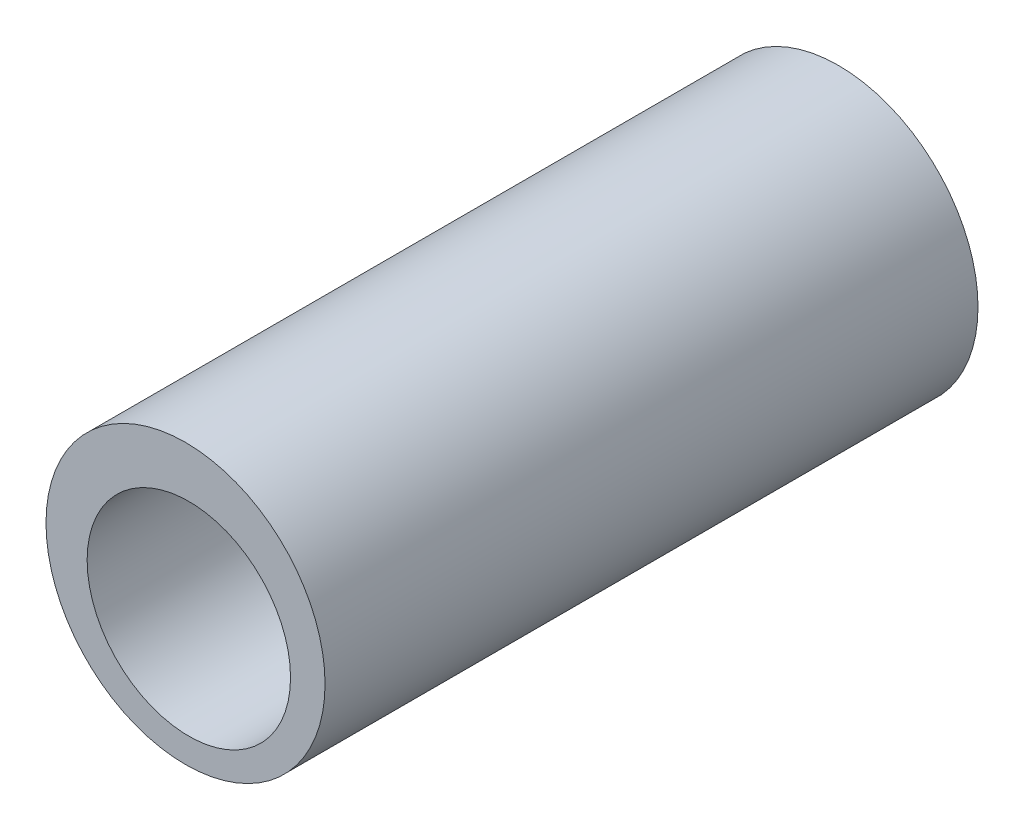
SolidWorks part; units mm, degrees
ref_plane "Front Plane" through (0, 0, 0) normal (0, 0, 1) x (1, 0, 0)
ref_plane "Top Plane" through (0, 0, 0) normal (0, 1, 0) x (1, 0, 0)
ref_plane "Right Plane" through (0, 0, 0) normal (1, 0, 0) x (0, 0, -1)
sketch "Sketch1" plane through (0, 0, 0) normal (0, 0, 1) x (1, 0, 0)
  circle A0 centre (-0.9041, 3.1644) radius 38.1
  dimension "D1" = 76.2
extrude "Boss-Extrude1" add sketch "Sketch1" along normal blind 178.308 contours A0
sketch "Sketch2" plane through (0, 0, 178.308) normal (0, 0, 1) x (1, 0, 0)
  circle A0 centre (0, 0) radius 27.7722
extrude "Cut-Extrude2" cut sketch "Sketch2" against normal blind 178.308 contours A0
